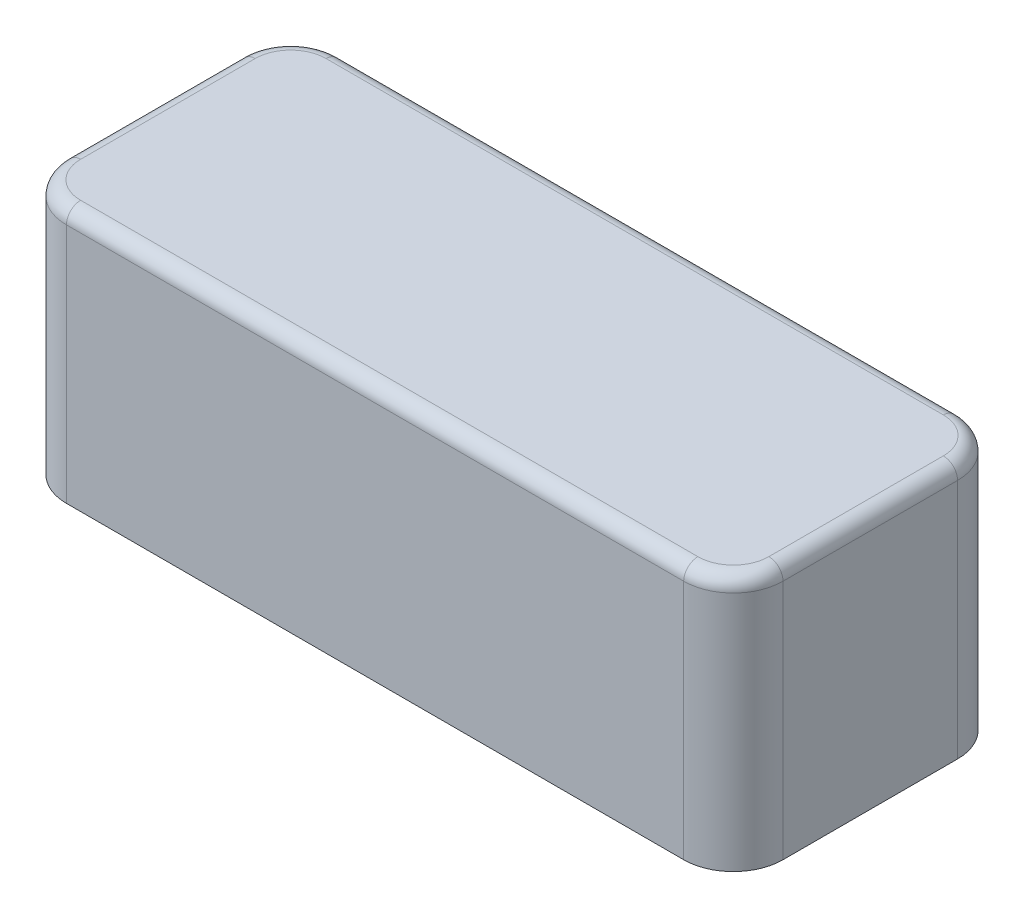
SolidWorks part; units mm, degrees
material "AISI 316 Stainless Steel Sheet (SS)"
ref_plane "Front Plane" through (0, 0, 0) normal (0, 0, 1) x (1, 0, 0)
ref_plane "Top Plane" through (0, 0, 0) normal (0, 1, 0) x (1, 0, 0)
ref_plane "Right Plane" through (0, 0, 0) normal (1, 0, 0) x (0, 0, -1)
sketch "Sketch1" plane through (0, 0, 0) normal (0, 1, 0) x (1, 0, 0)
  line L0 (-595, -283) -> (595, -283) construction
  line L1 (-435, -183) -> (435, -183)
  line L2 (-495, -123) -> (-495, 123)
  line L3 (-435, 183) -> (435, 183)
  line L4 (495, -123) -> (495, 123)
  line L5 (595, -183) -> (595, 183) construction
  line L6 (-595, 283) -> (595, 283) construction
  line L7 (-595, -283) -> (-595, 283) construction
  line L8 (-595, 0) -> (-739.9944, 0) construction
  line L9 (-595, -283) -> (-719.0818, -105) construction
  line L10 (-595, 283) -> (-719.0818, 105) construction
  line L11 (595, -283) -> (695, -283) construction
  line L12 (695, -283) -> (695, -183) construction
  line L13 (695, -183) -> (595, -183) construction
  line L14 (595, 283) -> (695, 283) construction
  line L15 (695, 283) -> (695, 183) construction
  line L16 (695, 183) -> (595, 183) construction
  line L18 (-420.0056, 105) -> (-495, 105) construction
  line L19 (-450.0056, 75) -> (-495, 75) construction
  line L20 (-450.0056, 75) -> (-450.0056, -75) construction
  line L21 (-450.0056, -75) -> (-495, -75) construction
  line L22 (-739.9944, 75) -> (-739.9944, -75) construction
  line L23 (-450.0056, 75) -> (-739.9944, -75) construction
  line L24 (-450.0056, -75) -> (-739.9944, 75) construction
  line L25 (-420.0056, 105) -> (-420.0056, -105) construction
  line L26 (-420.0056, -105) -> (-495, -105) construction
  line L27 (-420.0056, 105) -> (-739.9944, 105) construction
  line L28 (-679.0818, 95) -> (-679.0818, 85)
  line L29 (-420.0056, -105) -> (-739.9944, -105) construction
  line L30 (-679.0818, -85) -> (-679.0818, -95)
  line L31 (-689.0818, -105) -> (-719.0818, -105)
  line L32 (-689.0818, -75) -> (-739.9944, -75)
  line L33 (-450.0056, -75) -> (-739.9944, -75) construction
  line L34 (-689.0818, 105) -> (-719.0818, 105)
  line L35 (-689.0818, 75) -> (-739.9944, 75)
  line L36 (-450.0056, 75) -> (-739.9944, 75) construction
  line L37 (-255, -283) -> (-255, -213)
  line L38 (-255, -213) -> (-225, -213)
  line L39 (-225, -213) -> (-225, -283)
  line L40 (255, -283) -> (255, -213)
  line L41 (255, -213) -> (225, -213)
  line L42 (225, -213) -> (225, -283)
  line L43 (-495, 0) -> (495, 0) construction
  line L44 (-225, 213) -> (-225, 283)
  line L45 (-255, 213) -> (-225, 213)
  line L46 (-255, 283) -> (-255, 213)
  line L47 (225, 213) -> (225, 283)
  line L48 (255, 213) -> (225, 213)
  line L49 (255, 283) -> (255, 213)
  line L54 (-505, -123) -> (-505, 123)
  line L55 (-435, 193) -> (435, 193)
  line L56 (505, -123) -> (505, 123)
  line L57 (-435, -193) -> (435, -193)
  arc A0 (-679.0818, 95) -> (-689.0818, 105) centre (-689.0818, 95) ccw
  arc A1 (-679.0818, 85) -> (-689.0818, 75) centre (-689.0818, 85) cw
  arc A2 (-679.0818, -85) -> (-689.0818, -75) centre (-689.0818, -85) ccw
  arc A3 (-679.0818, -95) -> (-689.0818, -105) centre (-689.0818, -95) cw
  arc A4 (-495, -123) -> (-435, -183) centre (-435, -123) ccw
  arc A5 (-495, 123) -> (-435, 183) centre (-435, 123) cw
  arc A6 (495, -123) -> (435, -183) centre (435, -123) cw
  arc A7 (495, 123) -> (435, 183) centre (435, 123) ccw
  arc A8 (-505, 123) -> (-435, 193) centre (-435, 123) cw
  arc A9 (505, 123) -> (435, 193) centre (435, 123) ccw
  arc A10 (505, -123) -> (435, -193) centre (435, -123) cw
  arc A11 (-505, -123) -> (-435, -193) centre (-435, -123) ccw
  circle A12 centre (-408, -106.75) radius 49.1
  circle A13 centre (408, -106.75) radius 49.1
  circle A14 centre (-408, 106.75) radius 49.1
  circle A15 centre (408, 106.75) radius 49.1
  point P0 (0, 0)
  point P38 (-679.0818, 105)
  point P41 (-679.0818, 75)
  point P44 (-679.0818, -75)
  point P47 (-679.0818, -105)
  dimension "D4" = 10
  dimension "D2" = 30
  dimension "D3" = 40
  dimension "D5" = 1434.9944
extrude "Boss-Extrude1" add sketch "Sketch1" along normal blind 350 contours L54 A11 L57 A10 L56 A9 L55 A8 A7 L4 A6 L1 A4 L2 A5 L3
sketch "Sketch2" plane through (0, 350, 0) normal (0, 1, 0) x (1, 0, 0)
  line L0 (-435, 193) -> (435, 193) construction
  line L1 (-435, -193) -> (435, -193)
  line L2 (-505, -123) -> (-505, 123)
  line L3 (-435, 193) -> (435, 193)
  line L4 (505, -123) -> (505, 123)
  line L7 (505, -123) -> (505, 123) construction
  arc A0 (435, 193) -> (505, 123) centre (435, 123) cw
  arc A1 (435, -193) -> (505, -123) centre (435, -123) ccw
  arc A2 (-505, -123) -> (-435, -193) centre (-435, -123) ccw
  arc A3 (-505, 123) -> (-435, 193) centre (-435, 123) cw
  point P0 (0, 0)
  dimension "D1" = 70
extrude "Boss-Extrude2" add sketch "Sketch2" along normal blind 10
fillet "Fillet1" radius 20 8 edges at (-484.4975, 360, 172.4975) (-505, 360, 0) (-484.4975, 360, -172.4975) (0, 360, -193) (484.4975, 360, -172.4975) (505, 360, 0) (484.4975, 360, 172.4975) (0, 360, 193)
